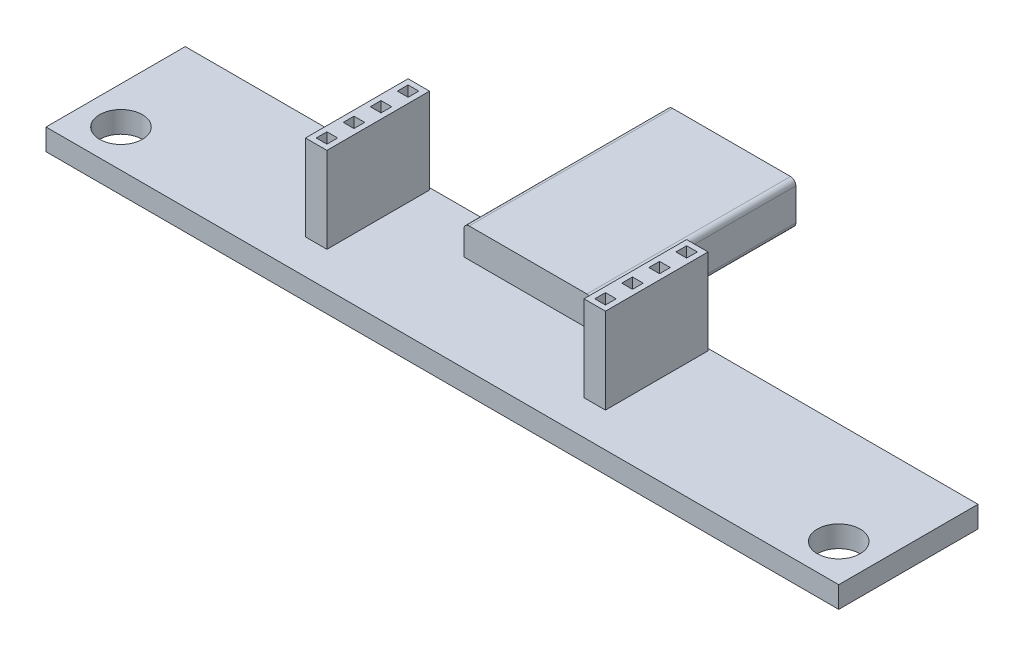
SolidWorks part; units mm, degrees
ref_plane "Front Plane" through (0, 0, 0) normal (0, 0, 1) x (1, 0, 0)
ref_plane "Top Plane" through (0, 0, 0) normal (0, 1, 0) x (1, 0, 0)
ref_plane "Right Plane" through (0, 0, 0) normal (1, 0, 0) x (0, 0, -1)
sketch "Sketch1" plane through (0, 0, 0) normal (0, 1, 0) x (1, 0, 0)
  line L0 (0, 0) -> (0, -3.9407) construction
  line L1 (37, -6.5) -> (-37, -6.5)
  line L2 (37, -6.5) -> (37, 6.5)
  line L3 (37, 6.5) -> (-37, 6.5)
  line L4 (-37, -6.5) -> (-37, 6.5)
  line L5 (37, -6.5) -> (-37, 6.5) construction
  line L6 (37, 6.5) -> (-37, -6.5) construction
  circle A0 centre (-33.5, -3) radius 2
  circle A1 centre (33.5, -3) radius 2
  point P0 (0, 0)
  dimension "D5" = 4
  dimension "D1" = 74
  dimension "D2" = 13
  dimension "D3" = 3.5
  dimension "D4" = 3.5
extrude "Boss-Extrude1" add sketch "Sketch1" along normal blind 2
sketch "Sketch2" plane through (0, 2, 0) normal (0, 1, 0) x (1, 0, 0)
  line L0 (37, 6.5) -> (-37, 6.5) construction
  line L1 (10, 6.3) -> (12, 6.3)
  line L2 (10, 6.3) -> (10, -3.2775)
  line L3 (10, -3.2775) -> (12, -3.2775)
  line L4 (12, 6.3) -> (12, -3.2775)
  line L5 (37, -6.5) -> (37, 6.5) construction
  line L6 (-2, 6.5) -> (-2, -3.5) construction
  line L7 (-15.5, 5.8) -> (-14.5, 4.8) construction
  line L8 (11, 6.3) -> (11, -3.2775) construction
  line L9 (11.5, 2.2742) -> (11.5, 3.2742)
  line L10 (11.5, 4.8) -> (10.5, 4.8)
  line L11 (11.5, 4.8) -> (11.5, 5.8)
  line L12 (11.5, 5.8) -> (10.5, 5.8)
  line L13 (10.5, 4.8) -> (10.5, 5.8)
  line L14 (11.5, 4.8) -> (10.5, 5.8) construction
  line L15 (11.5, 5.8) -> (10.5, 4.8) construction
  line L16 (11.5, 2.2742) -> (10.5, 2.2742)
  line L17 (10.5, 2.2742) -> (10.5, 3.2742)
  line L18 (11.5, 3.2742) -> (10.5, 3.2742)
  line L19 (11.5, -0.2517) -> (11.5, 0.7483)
  line L20 (11.5, -0.2517) -> (10.5, -0.2517)
  line L21 (10.5, -0.2517) -> (10.5, 0.7483)
  line L22 (11.5, 0.7483) -> (10.5, 0.7483)
  line L23 (11.5, -2.7775) -> (11.5, -1.7775)
  line L24 (11.5, -2.7775) -> (10.5, -2.7775)
  line L25 (10.5, -2.7775) -> (10.5, -1.7775)
  line L26 (11.5, -1.7775) -> (10.5, -1.7775)
  line L27 (-15.5, 4.8) -> (-14.5, 5.8) construction
  line L28 (-15, 6.3) -> (-15, -3.2775) construction
  line L29 (-15.5, -1.7775) -> (-14.5, -1.7775)
  line L30 (-14.5, -2.7775) -> (-14.5, -1.7775)
  line L31 (-15.5, -2.7775) -> (-14.5, -2.7775)
  line L32 (-15.5, -2.7775) -> (-15.5, -1.7775)
  line L33 (-15.5, 0.7483) -> (-14.5, 0.7483)
  line L34 (-14.5, -0.2517) -> (-14.5, 0.7483)
  line L35 (-15.5, -0.2517) -> (-14.5, -0.2517)
  line L36 (-15.5, -0.2517) -> (-15.5, 0.7483)
  line L37 (-15.5, 3.2742) -> (-14.5, 3.2742)
  line L38 (-14.5, 2.2742) -> (-14.5, 3.2742)
  line L39 (-15.5, 2.2742) -> (-14.5, 2.2742)
  line L40 (-14.5, 4.8) -> (-14.5, 5.8)
  line L41 (-15.5, 5.8) -> (-14.5, 5.8)
  line L42 (-15.5, 4.8) -> (-15.5, 5.8)
  line L43 (-15.5, 4.8) -> (-14.5, 4.8)
  line L44 (-15.5, 2.2742) -> (-15.5, 3.2742)
  line L45 (-16, 6.3) -> (-16, -3.2775)
  line L46 (-14, -3.2775) -> (-16, -3.2775)
  line L47 (-14, 6.3) -> (-14, -3.2775)
  line L48 (-14, 6.3) -> (-16, 6.3)
  point P10 (11, 5.3)
  point P51 (-15, 5.3)
  point P52 (0, 0)
  point P53 (0, 0)
  dimension "D1" = 2
  dimension "D2" = 0.5
  dimension "D3" = 25
  dimension "D4" = 12
  dimension "D5" = 0.5
  dimension "D6" = 1
  dimension "D7" = 1
  dimension "D9" = 0.2
  dimension "D8" = 4
extrude "Boss-Extrude2" add sketch "Sketch2" along normal blind 8
ref_plane "Plane1" through (0, 0.75, 0) normal (0, 1, 0) x (1, 0, 0)
sketch "Sketch3" plane through (0, 0.75, 0) normal (0, 1, 0) x (1, 0, 0)
  line L0 (37, -6.5) -> (37, 6.5) construction
  line L1 (5, 2.5) -> (-7, 2.5)
  line L2 (5, 2.5) -> (5, 21.5)
  line L3 (5, 21.5) -> (-7, 21.5)
  line L4 (-7, 2.5) -> (-7, 21.5)
  line L5 (37, 6.5) -> (-37, 6.5) construction
  dimension "D1" = 32
  dimension "D2" = 12
  dimension "D3" = 19
  dimension "D4" = 4
extrude "Boss-Extrude3" add sketch "Sketch3" along normal blind 4
fillet "Fillet1" radius 0.5 4 edges at (-7, 0.75, -14) (5, 0.75, -14) (-7, 4.75, -12) (5, 4.75, -12)
